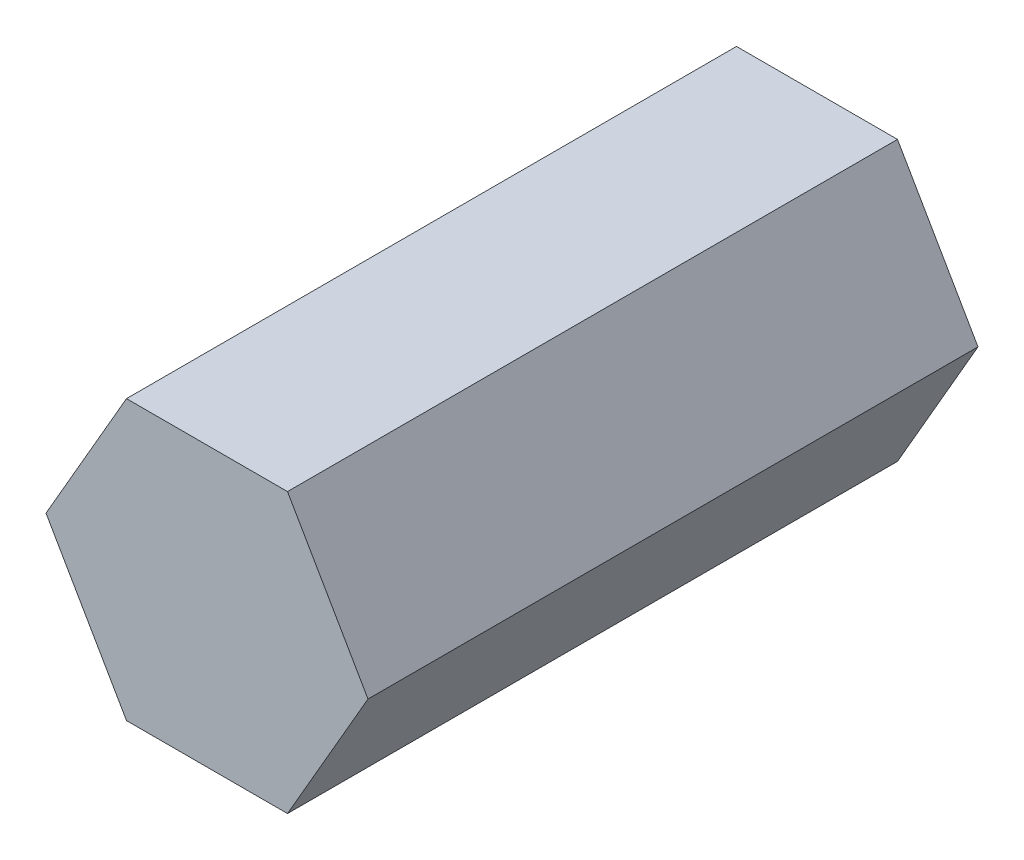
SolidWorks part; units mm, degrees
ref_plane "前视基准面" through (0, 0, 0) normal (0, 0, 1) x (1, 0, 0)
ref_plane "上视基准面" through (0, 0, 0) normal (0, 1, 0) x (1, 0, 0)
ref_plane "右视基准面" through (0, 0, 0) normal (1, 0, 0) x (0, 0, -1)
sketch "草图1" plane through (0, 0, 0) normal (0, 0, 1) x (1, 0, 0)
  line L0 (-28.6627, 0) -> (33.6774, 0) construction
  line L1 (0.9238, -1.6) -> (1.8475, 0)
  line L2 (1.8475, 0) -> (0.9238, 1.6)
  line L3 (0.9238, 1.6) -> (-0.9238, 1.6)
  line L4 (-0.9238, 1.6) -> (-1.8475, 0)
  line L5 (-1.8475, 0) -> (-0.9238, -1.6)
  line L6 (-0.9238, -1.6) -> (0.9238, -1.6)
  circle A0 centre (0, 0) radius 1.6 construction
  dimension "D1" = 3.2
extrude "拉伸1" add sketch "草图1" along normal blind 7
sketch "草图2" plane through (0, 0, 7) normal (0, 0, 1) x (1, 0, 0)
  circle A0 centre (0, 0) radius 1
  dimension "D1" = 2
hole_wizard "M2 螺纹孔1" positions "3D草图2" profile "草图5" tap size "M2" standard "Iso"
sketch3d "3D草图2"
  point P0 (0, 0, 0)
  point P2 (0, 0, 0)
  point P3 (0, 0, 0)
  point P4 (0, 0, 0)
cosmetic thread "孔螺蚊线1" parameters "D1"=4, "D2"=2
sketch "草图5" plane through (0, 0, 0) normal (1, 0, 0) x (0, 1, 0)
  line L0 (0, 0) -> (0, 6.4807)
  line L1 (0, 6.4807) -> (0.8, 6)
  line L2 (0.8, 6) -> (0.8, 0)
  line L5 (0.8, 0) -> (0, 0)
  line L10 (0, 6.4807) -> (-0.8, 6) construction
  line L11 (0, -6.35) -> (0, 107.95) construction
  dimension "蹟恇謂郰芛眻噤" = 1.6
  dimension "蹟恇謂郰芛旮僅" = 6
  dimension "絳芛褒僅" = 118
cosmetic thread "孔螺蚊线2" parameters "D1"=4, "D2"=2
cosmetic thread "孔螺蚊线3" parameters "D1"=4, "D2"=2
cosmetic thread "孔螺蚊线4" parameters "D1"=4, "D2"=2
sketch "草图6" plane through (0, 0, 0) normal (0, 0, -1) x (-1, 0, 0)
  circle A0 centre (0, 0) radius 1.5
  dimension "D1" = 3
extrude "拉伸3" [suppressed] add sketch "草图6" along normal blind 10
